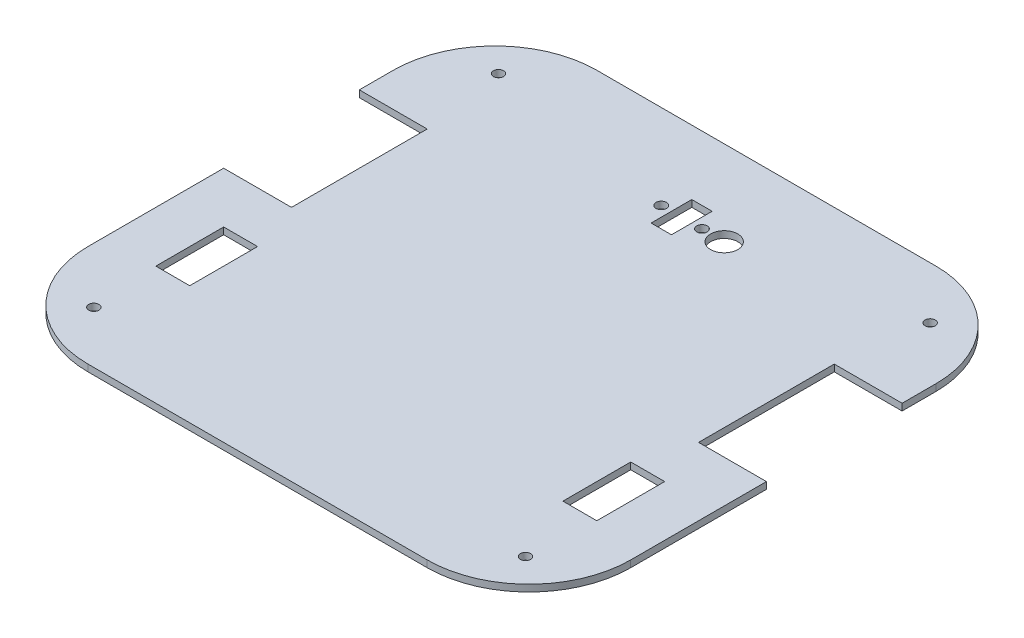
SolidWorks part; units mm, degrees
ref_plane "Front Plane" through (0, 0, 0) normal (0, 0, 1) x (1, 0, 0)
ref_plane "Top Plane" through (0, 0, 0) normal (0, 1, 0) x (1, 0, 0)
ref_plane "Right Plane" through (0, 0, 0) normal (1, 0, 0) x (0, 0, -1)
sketch "Sketch1" plane through (0, 0, 0) normal (0, 1, 0) x (1, 0, 0)
  line L0 (-80, 35) -> (-60, 35)
  line L1 (-50, -75) -> (50, -75)
  line L2 (-80, -45) -> (-80, -5)
  line L3 (-50, 75) -> (50, 75)
  line L4 (80, -45) -> (80, -5)
  line L5 (-80, -75) -> (80, 75) construction
  line L6 (-80, 75) -> (80, -75) construction
  line L7 (-60, 35) -> (-60, -5)
  line L8 (-60, -5) -> (-80, -5)
  line L9 (0, 75) -> (0, 0) construction
  line L10 (60, -5) -> (80, -5)
  line L11 (60, 35) -> (60, -5)
  line L12 (80, 35) -> (60, 35)
  line L13 (-80, 35) -> (-80, 45)
  line L14 (80, 35) -> (80, 45)
  line L15 (0, 0) -> (69.2486, 0) construction
  arc A0 (50, -75) -> (80, -45) centre (50, -45) ccw
  arc A1 (-50, -75) -> (-80, -45) centre (-50, -45) cw
  arc A2 (50, 75) -> (80, 45) centre (50, 45) cw
  arc A3 (-80, 45) -> (-50, 75) centre (-50, 45) cw
  circle A4 centre (-63.621, 59.6447) radius 1.5
  circle A5 centre (63.621, 59.6447) radius 1.5
  circle A6 centre (63.621, -59.6447) radius 1.5
  circle A7 centre (-63.621, -59.6447) radius 1.5
  point P0 (0, 0)
  dimension "D3" = 30
  dimension "D7" = 3
  dimension "D8" = 20
  dimension "D1" = 150
  dimension "D2" = 160
  dimension "D4" = 20
  dimension "D5" = 40
  dimension "D6" = 10
extrude "Boss-Extrude1" add sketch "Sketch1" along normal blind 2
sketch "Sketch2" plane through (0, 2, 0) normal (0, 1, 0) x (1, 0, 0)
  line L0 (-6, 50) -> (6, 50)
  line L1 (0, 75) -> (0, 25.7423) construction
  line L2 (-3, 44) -> (3, 44)
  line L3 (-3, 44) -> (-3, 56)
  line L4 (-3, 56) -> (3, 56)
  line L5 (3, 44) -> (3, 56)
  line L6 (-3, 44) -> (3, 56) construction
  line L7 (-3, 56) -> (3, 44) construction
  line L8 (50, 75) -> (-50, 75) construction
  line L9 (7.55, 50) -> (12.55, 50)
  circle A0 centre (-6, 50) radius 1.55
  circle A2 centre (6, 50) radius 1.55
  circle A3 centre (12.55, 50) radius 4
  point P4 (0, 50)
  dimension "D1" = 3.1
  dimension "D2" = 3.1
  dimension "D7" = 8
  dimension "D3" = 12
  dimension "D4" = 6
  dimension "D5" = 12
  dimension "D6" = 5
  dimension "D8" = 0
  dimension "D9" = 25
  dimension "D10" = 0
extrude "Cut-Extrude1" cut sketch "Sketch2" against normal blind 10
sketch "Sketch3" plane through (0, 2, 0) normal (0, 1, 0) x (1, 0, 0)
  line L0 (-60, -5) -> (-60, -46.485) construction
  line L1 (-60, -5) -> (-80, -5) construction
  line L2 (-65, -20) -> (-55, -20)
  line L3 (-65, -20) -> (-65, -40)
  line L4 (-65, -40) -> (-55, -40)
  line L5 (-55, -20) -> (-55, -40)
  line L6 (-65, -20) -> (-55, -40) construction
  line L7 (-65, -40) -> (-55, -20) construction
  line L8 (0, -75) -> (0, -15.0905) construction
  line L9 (-50, -75) -> (50, -75) construction
  line L10 (65, -20) -> (55, -40) construction
  line L11 (65, -40) -> (55, -20) construction
  line L12 (65, -20) -> (55, -20)
  line L13 (65, -20) -> (65, -40)
  line L14 (65, -40) -> (55, -40)
  line L15 (55, -20) -> (55, -40)
  point P3 (-60, -30)
  dimension "D1" = 10
  dimension "D2" = 20
  dimension "D3" = 15
extrude "Cut-Extrude2" cut sketch "Sketch3" against normal blind 10
